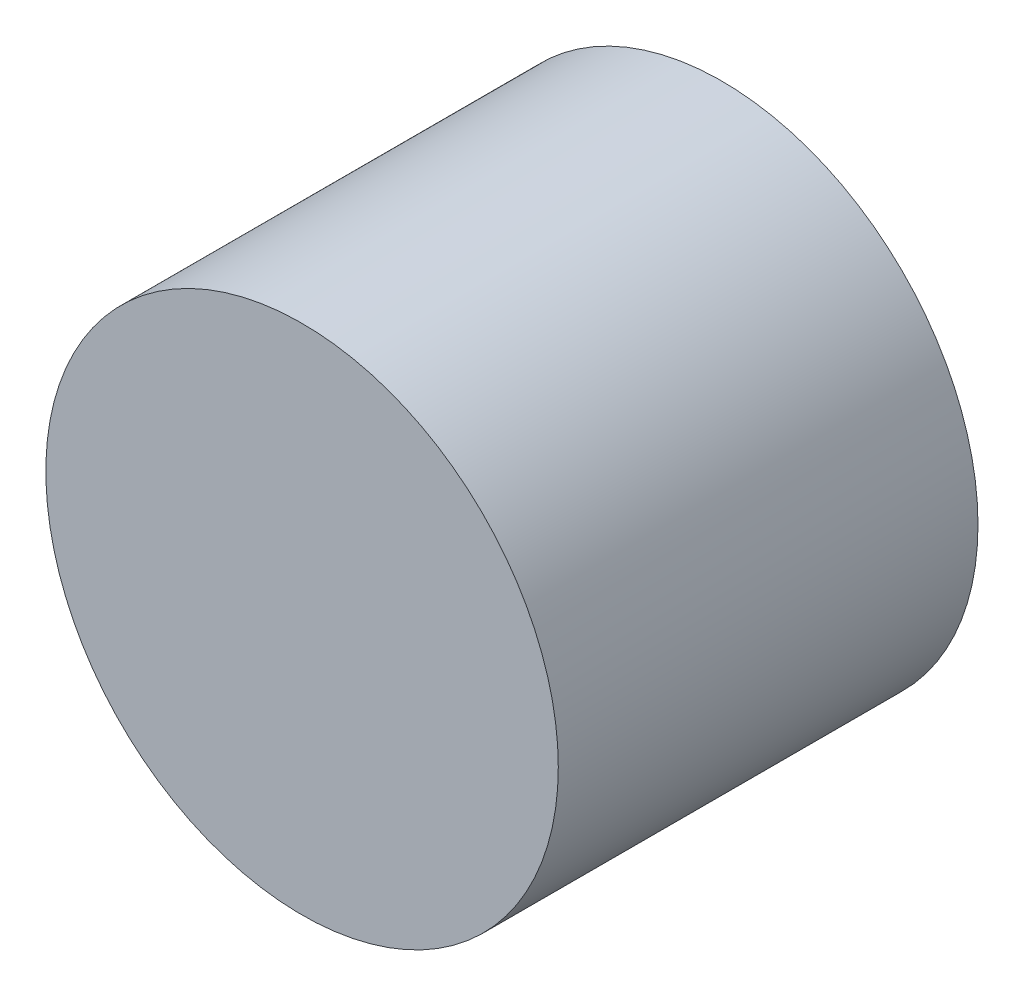
SolidWorks part; units mm, degrees
ref_plane "Front Plane" through (0, 0, 0) normal (0, 0, 1) x (1, 0, 0)
ref_plane "Top Plane" through (0, 0, 0) normal (0, 1, 0) x (1, 0, 0)
ref_plane "Right Plane" through (0, 0, 0) normal (1, 0, 0) x (0, 0, -1)
sketch "Sketch1" plane through (0, 0, 0) normal (0, 0, 1) x (1, 0, 0)
  circle A0 centre (6.787, -3.953) radius 8.8061
  dimension "D1" = 17.6123
extrude "Boss-Extrude1" add sketch "Sketch1" along normal blind 14.4241
